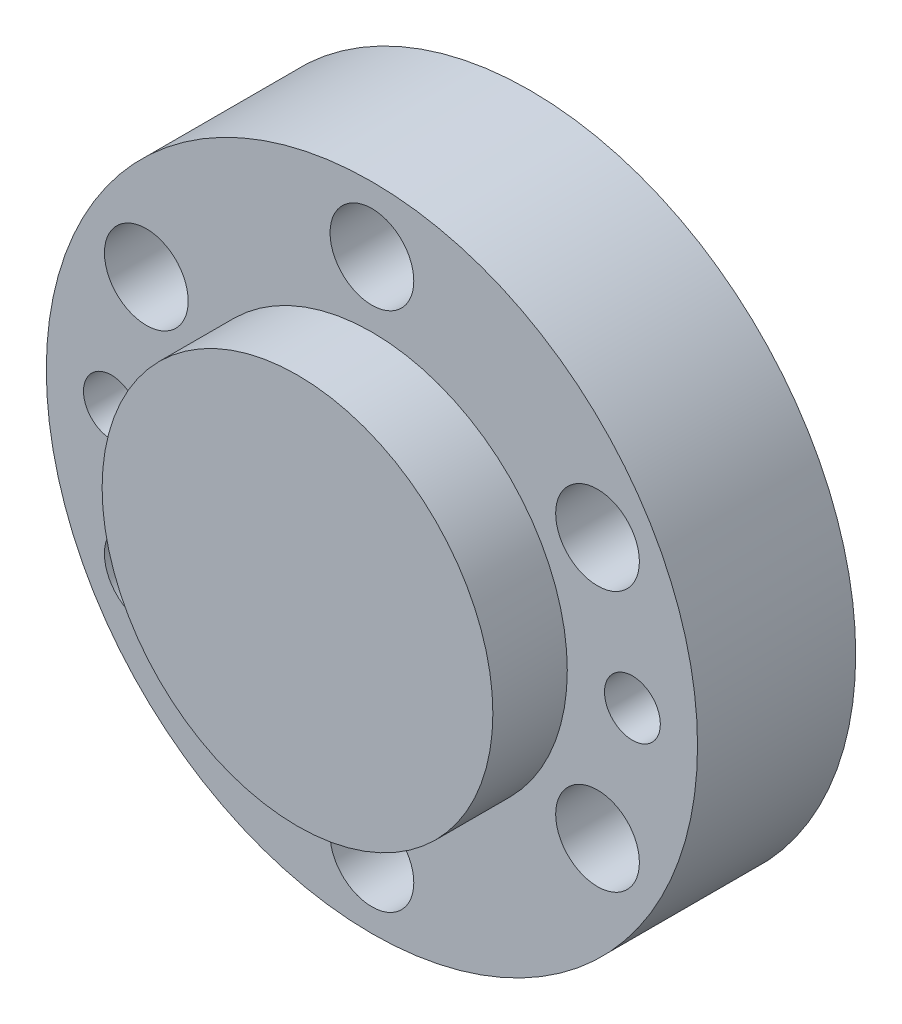
SolidWorks part; units mm, degrees
material "PA Type 6"
ref_plane "Front Plane" through (0, 0, 0) normal (0, 0, 1) x (1, 0, 0)
ref_plane "Top Plane" through (0, 0, 0) normal (0, 1, 0) x (1, 0, 0)
ref_plane "Right Plane" through (0, 0, 0) normal (1, 0, 0) x (0, 0, -1)
sketch "Sketch1" plane through (0, 0, 0) normal (0, 1, 0) x (1, 0, 0)
  line L0 (19, 8.5) -> (19, 7.5)
  line L1 (19, 7.5) -> (17.5, 7.5)
  line L2 (17.5, 7.5) -> (17.5, 1)
  line L3 (17.5, 1) -> (19, 1)
  line L4 (19, 1) -> (19, 0)
  line L5 (19, 0) -> (10.5, 0)
  line L6 (10.5, 0) -> (10.5, -4)
  line L7 (10.5, -4) -> (0, -4)
  line L8 (0, -4) -> (0, 8.5)
  line L9 (0, 8.5) -> (19, 8.5)
  dimension "D1" = 10.5
  dimension "D2" = 4
  dimension "D3" = 17.5
  dimension "D4" = 1.5
  dimension "D5" = 6.5
  dimension "D6" = 1
revolve "Revolve1" add sketch "Sketch1" angle 360 about L8
sketch "Sketch4" plane through (0, 0, -8.5) normal (0, 0, -1) x (-1, 0, 0)
  circle A0 centre (0, 0) radius 14
  point P5 (0, 14)
  point P11 (12.1244, 7)
  point P12 (12.1244, -7)
  point P13 (0, -14)
  point P14 (-12.1244, -7)
  point P15 (-12.1244, 7)
  dimension "D1" = 28
  dimension "D2" = 6
hole_wizard "M4 Clearance Hole1" positions "Sketch4" profile "Sketch5" hole size "M4" standard "DIN" end condition through all
sketch "Sketch5" plane through (12.1244, 7, -8.5) normal (1, 0, 0) x (0, 1, 0)
  line L0 (0, 0) -> (0, 12.5)
  line L1 (0, 12.5) -> (2.25, 12.5)
  line L2 (2.25, 12.5) -> (2.25, 0)
  line L5 (2.25, 0) -> (0, 0)
  line L11 (0, -6.35) -> (0, 107.95) construction
  dimension "Thru Hole Dia." = 4.5
  dimension "Thru Hole Depth" = 12.5
sketch "Sketch8" plane through (0, 0, -8.5) normal (0, 0, -1) x (-1, 0, 0)
  circle A0 centre (0, 0) radius 14
  point P6 (-14, 0)
  point P8 (14, 0)
hole_wizard "Ø3.0mm Dowel Hole1" positions "Sketch8" profile "Sketch7" hole size "Ø3.0" standard "DIN" end condition through all
sketch "Sketch7" plane through (-14, 0, -8.5) normal (1, 0, 0) x (0, 1, 0)
  line L0 (0, 0) -> (0, 12.5)
  line L1 (0, 12.5) -> (1.5, 12.5)
  line L2 (1.5, 12.5) -> (1.5, 0)
  line L5 (1.5, 0) -> (0, 0)
  line L11 (0, -6.35) -> (0, 107.95) construction
  dimension "Thru Hole Dia." = 3
  dimension "Thru Hole Depth" = 12.5
sketch "Sketch9" plane through (0, 0, 0) normal (0, 0, 1) x (1, 0, 0)
  circle A0 centre (0, 0) radius 17.5 construction
  circle A1 centre (0, 0) radius 19 construction
  circle A2 centre (0, 0) radius 17.5
  circle A3 centre (0, 0) radius 19
  circle A4 centre (0, 0) radius 19
  circle M11 centre (0, 0) radius 19
extrude "Cut-Extrude1" cut sketch "Sketch9" against normal through all contours A2 M11
